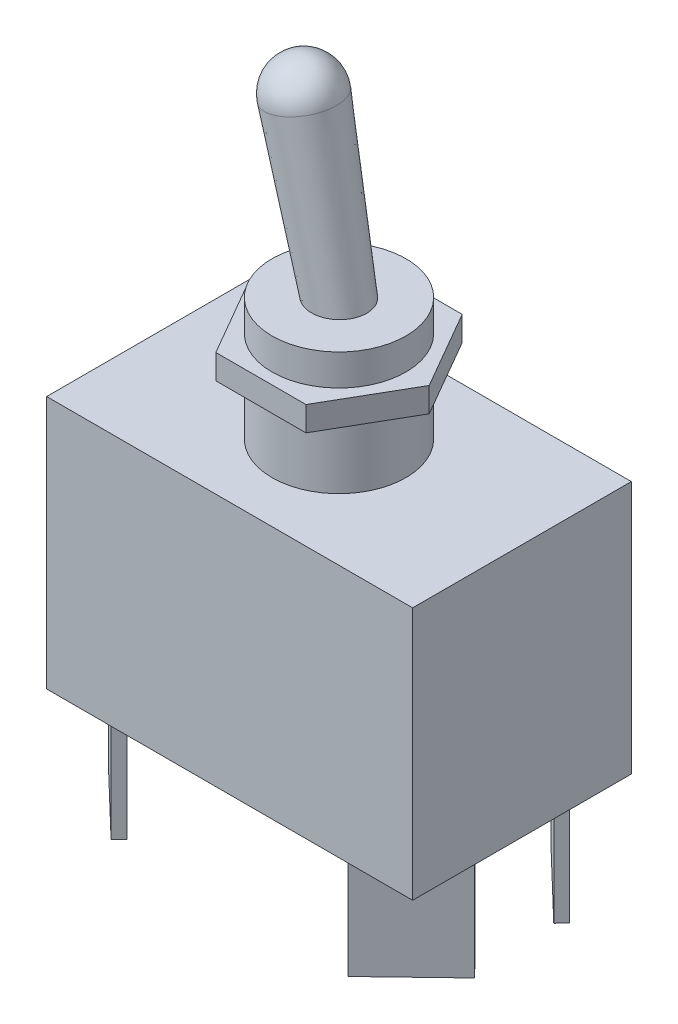
SolidWorks part; units mm, degrees
ref_plane "Plan de face" through (0, 0, 0) normal (0, 0, 1) x (1, 0, 0)
ref_plane "Plan de dessus" through (0, 0, 0) normal (0, 1, 0) x (1, 0, 0)
ref_plane "Plan de droite" through (0, 0, 0) normal (1, 0, 0) x (0, 0, -1)
sketch "Esquisse1" plane through (0, 0, 0) normal (0, 1, 0) x (1, 0, 0)
  line L1 (-16.4, 9.8) -> (16.4, 9.8)
  line L2 (-16.4, 9.8) -> (-16.4, -9.8)
  line L3 (-16.4, -9.8) -> (16.4, -9.8)
  line L4 (16.4, 9.8) -> (16.4, -9.8)
  point P4 (0, 9.8)
  point P6 (-16.4, 0)
  dimension "D1" = 19.6
  dimension "D2" = 32.8
extrude "Boss.-Extru.1" add sketch "Esquisse1" along normal blind 22.7
sketch "Esquisse2" plane through (0, 22.7, 0) normal (0, 1, 0) x (1, 0, 0)
  circle A0 centre (0, 0) radius 6
  dimension "D1" = 12
extrude "Boss.-Extru.2" add sketch "Esquisse2" along normal blind 11
sketch "Esquisse3" plane through (0, 0, 0) normal (0, 0, 1) x (1, 0, 0)
  line L0 (0, 33.7) -> (-3.8093, 50.8828)
  line L1 (6, 33.7) -> (-6, 33.7) construction
  line L2 (-2.1024, 32.0949) -> (0, 33.7)
  line L3 (0, 33.7) -> (0, 45.342) construction
  line L4 (-2.1024, 32.0949) -> (-6.0634, 47.1897)
  arc A0 (-3.8093, 50.8828) -> (-6.0634, 47.1897) centre (-3.1595, 47.9518) ccw
  dimension "D1" = 2.4
  dimension "D2" = 12.5
  dimension "D3" = 3
  dimension "D4" = 17.6
revolve "Révolution1" add sketch "Esquisse3" angle 360 about L0
sketch "Esquisse4" plane through (0, 0, 0) normal (0, -1, 0) x (1, 0, 0)
  line L0 (-16.4, 4.2621) -> (-10.6267, 9.8)
  line L1 (-10.6267, 9.8) -> (-9.9344, 9.0783)
  line L2 (-9.9344, 9.0783) -> (-15.7078, 3.5404)
  line L3 (-15.7078, 3.5404) -> (-16.4, 4.2621)
  line L4 (0, 0) -> (0, 2.9226) construction
  line L5 (0, 0) -> (2.1615, 0) construction
  line L6 (15.7078, 3.5404) -> (16.4, 4.2621)
  line L7 (9.9344, 9.0783) -> (15.7078, 3.5404)
  line L8 (10.6267, 9.8) -> (9.9344, 9.0783)
  line L9 (16.4, 4.2621) -> (10.6267, 9.8)
  line L10 (16.4, -4.2621) -> (10.6267, -9.8)
  line L11 (10.6267, -9.8) -> (9.9344, -9.0783)
  line L12 (9.9344, -9.0783) -> (15.7078, -3.5404)
  line L13 (15.7078, -3.5404) -> (16.4, -4.2621)
  line L14 (-15.7078, -3.5404) -> (-16.4, -4.2621)
  line L15 (-9.9344, -9.0783) -> (-15.7078, -3.5404)
  line L16 (-10.6267, -9.8) -> (-9.9344, -9.0783)
  line L17 (-16.4, -4.2621) -> (-10.6267, -9.8)
  line L18 (-16.4, 9.8) -> (16.4, 9.8) construction
  line L19 (-16.4, -9.8) -> (-16.4, 9.8) construction
  dimension "D1" = 1
  dimension "D2" = 8
extrude "Boss.-Extru.3" add sketch "Esquisse4" along normal blind 8.8
sketch "Esquisse5" plane through (0, 22.7, 0) normal (0, 1, 0) x (1, 0, 0)
  line L1 (8.0829, 0) -> (4.0415, 7)
  line L2 (4.0415, 7) -> (-4.0415, 7)
  line L3 (-4.0415, 7) -> (-8.0829, 0)
  line L4 (-8.0829, 0) -> (-4.0415, -7)
  line L5 (-4.0415, -7) -> (4.0415, -7)
  line L6 (4.0415, -7) -> (8.0829, 0)
  circle A0 centre (0, 0) radius 7 construction
  dimension "D1" = 14
extrude "Boss.-Extru.4" add sketch "Esquisse5" along normal blind 2.2 from offset 6 separate body
